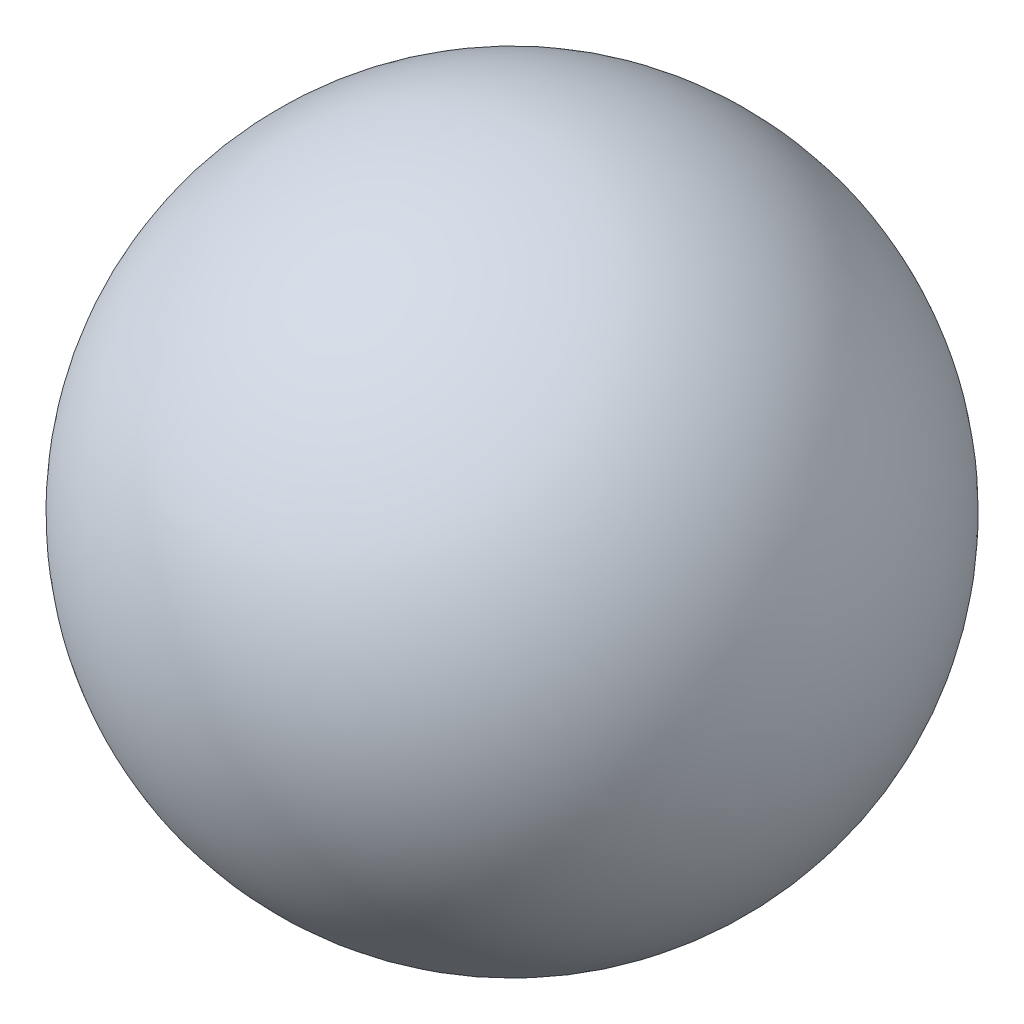
SolidWorks part; units mm, degrees
ref_plane "Front Plane" through (0, 0, 0) normal (0, 0, 1) x (1, 0, 0)
ref_plane "Top Plane" through (0, 0, 0) normal (0, 1, 0) x (1, 0, 0)
ref_plane "Right Plane" through (0, 0, 0) normal (1, 0, 0) x (0, 0, -1)
sketch "Sketch1" plane through (0, 0, 0) normal (0, 1, 0) x (1, 0, 0)
  line L0 (0, -2.25) -> (0, 2.25)
  arc A0 (0, -2.25) -> (0, 2.25) centre (0, 0) ccw
  dimension "D1" = 4.5
revolve "Revolve5" add sketch "Sketch1" angle 360 about L0
